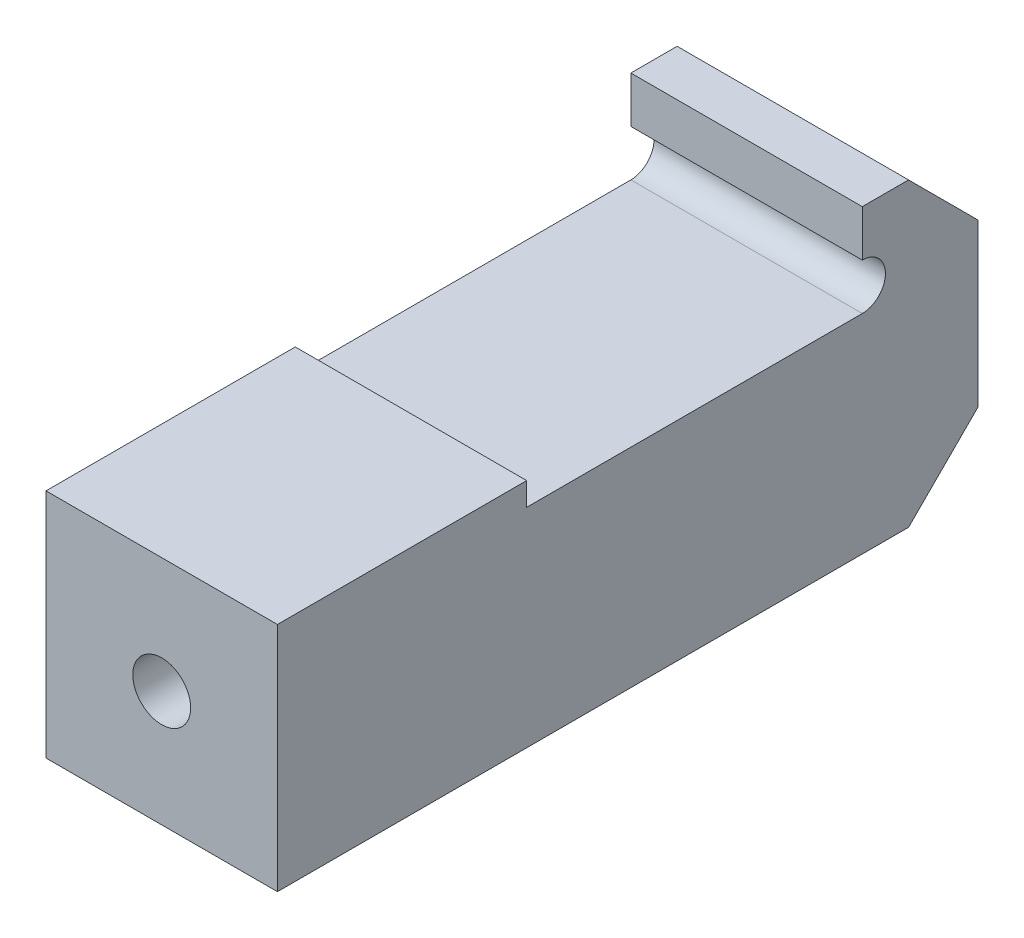
SolidWorks part; units mm, degrees
ref_plane "Front Plane" through (0, 0, 0) normal (0, 0, 1) x (1, 0, 0)
ref_plane "Top Plane" through (0, 0, 0) normal (0, 1, 0) x (1, 0, 0)
ref_plane "Right Plane" through (0, 0, 0) normal (1, 0, 0) x (0, 0, -1)
sketch "Sketch1" plane through (0, 0, 0) normal (1, 0, 0) x (0, 0, -1)
  line L0 (0, 1) -> (0, 3)
  line L1 (0, -1) -> (-14.5, -1)
  line L2 (-14.5, -1) -> (-14.5, 0)
  line L3 (-14.5, 0) -> (-25.27, 0)
  line L4 (-25.27, 0) -> (-25.27, -10)
  line L5 (-25.27, -10) -> (5, -10)
  line L10 (5, -10) -> (5, 3)
  line L11 (5, 3) -> (0, 3)
  arc A0 (0, -1) -> (0, 1) centre (0, 0) ccw
  dimension "D2" = 2
  dimension "D1" = 10
  dimension "D3" = 2
  dimension "D5" = 14.5
  dimension "D6" = 25.27
  dimension "D9" = 5
extrude "Boss-Extrude1" add sketch "Sketch1" against normal blind 10
chamfer "Chamfer1" distance 3 angle 45 2 edges at (-5, 3, -5) (-5, -10, -5)
sketch "Sketch2" plane through (0, 0, 25.27) normal (0, 0, 1) x (1, 0, 0)
  line L0 (-5, 0) -> (-5, -5) construction
  line L1 (-10, 0) -> (0, 0) construction
  dimension "D1" = 5
hole_wizard "M3x0.5 Tapped Hole1" positions "3DSketch1" profile "Sketch4" tap size "M3x0.5" standard "ANSI Metric"
sketch3d "3DSketch1"
  point P0 (-5, -5, 25.27)
sketch "Sketch4" plane through (-5, -5, 25.27) normal (1, 0, 0) x (0, -1, 0)
  line L0 (0, 0) -> (0, 15.2511)
  line L1 (0, 15.2511) -> (1.25, 14.5)
  line L2 (1.25, 14.5) -> (1.25, 0)
  line L5 (1.25, 0) -> (0, 0)
  line L10 (0, 15.2511) -> (-1.25, 14.5) construction
  line L11 (0, -6.35) -> (0, 107.95) construction
  dimension "Tap Drill Dia." = 2.5
  dimension "Tap Drill Depth" = 14.5
  dimension "Drill Angle" = 118
cosmetic thread "Hole Thread1" parameters "D1"=12, "D2"=3
